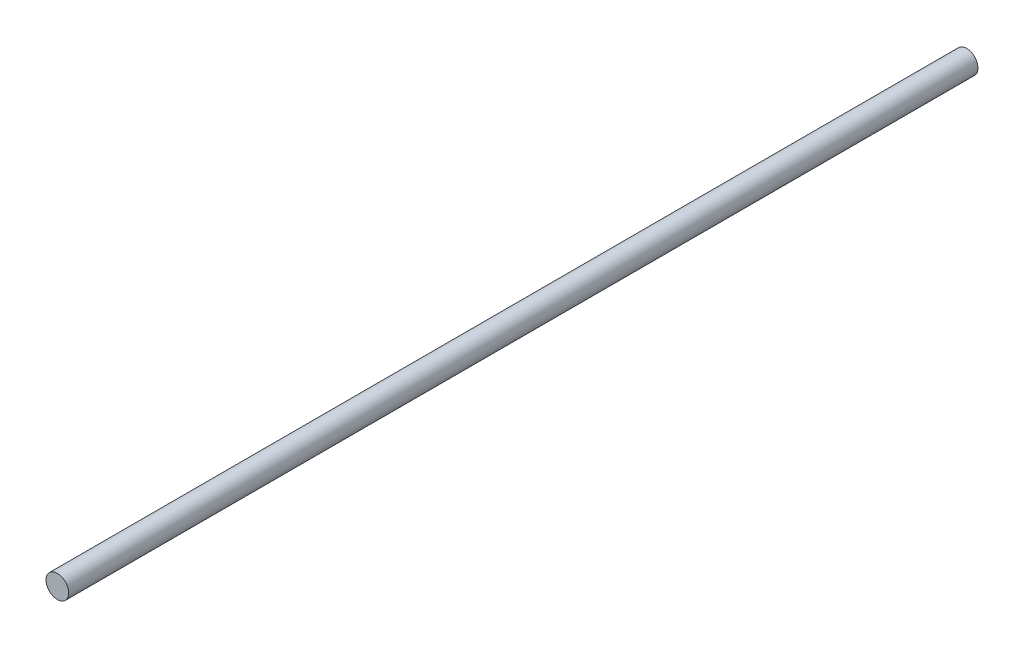
SolidWorks part; units mm, degrees
ref_plane "Front Plane" through (0, 0, 0) normal (0, 0, 1) x (1, 0, 0)
ref_plane "Top Plane" through (0, 0, 0) normal (0, 1, 0) x (1, 0, 0)
ref_plane "Right Plane" through (0, 0, 0) normal (1, 0, 0) x (0, 0, -1)
sketch "Sketch1" plane through (0, 0, 0) normal (0, 0, 1) x (1, 0, 0)
  circle A0 centre (0, 0) radius 2.5
  dimension "D1" = 5
extrude "Boss-Extrude1" add sketch "Sketch1" along normal blind 200
